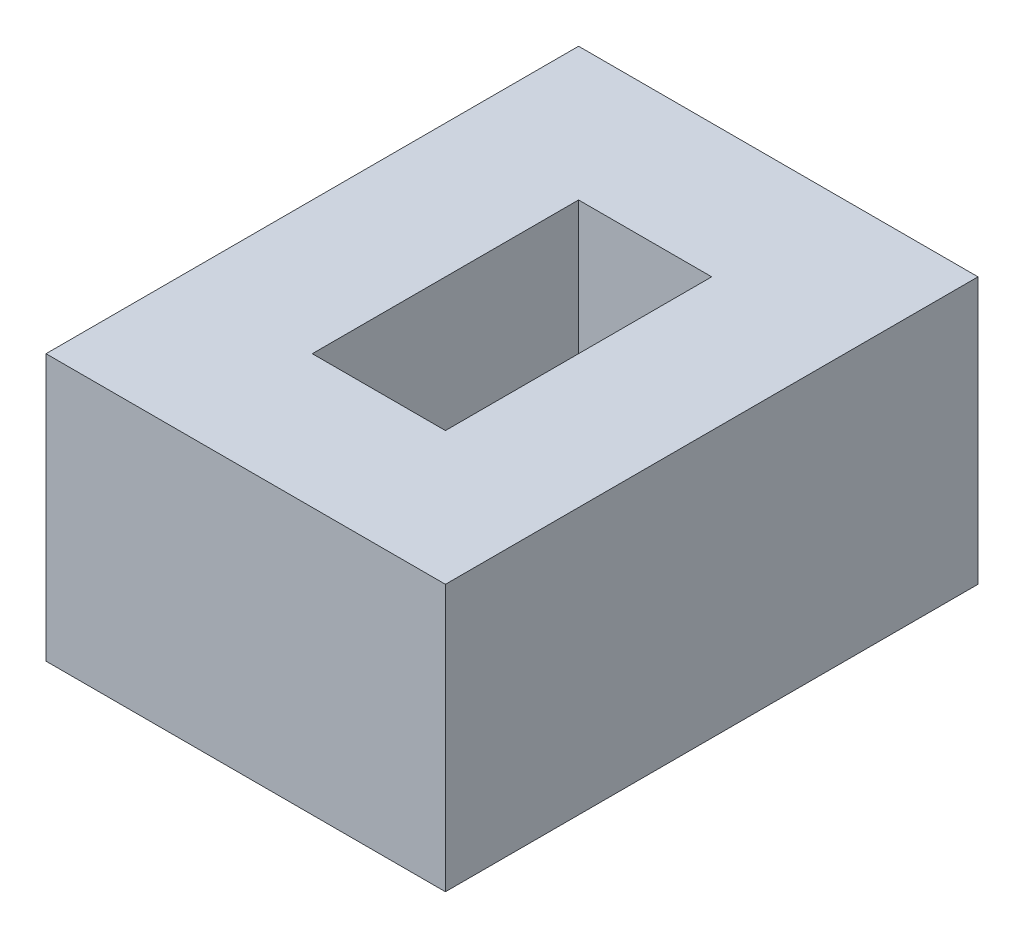
SolidWorks part; units mm, degrees
ref_plane "前视基准面" through (0, 0, 0) normal (0, 0, 1) x (1, 0, 0)
ref_plane "上视基准面" through (0, 0, 0) normal (0, 1, 0) x (1, 0, 0)
ref_plane "右视基准面" through (0, 0, 0) normal (1, 0, 0) x (0, 0, -1)
sketch "草图1" plane through (0, 0, 0) normal (0, 1, 0) x (1, 0, 0)
  line L0 (0, 0) -> (5, 0)
  line L1 (0, 0) -> (0, -10)
  line L2 (5, 0) -> (5, -10)
  line L3 (0, -10) -> (5, -10)
  line L4 (-5, 5) -> (-5, -15)
  line L5 (-5, -15) -> (10, -15)
  line L6 (10, 5) -> (10, -15)
  line L7 (-5, 5) -> (10, 5)
  dimension "D1" = 5
extrude "凸台-拉伸1" add sketch "草图1" along normal blind 10
